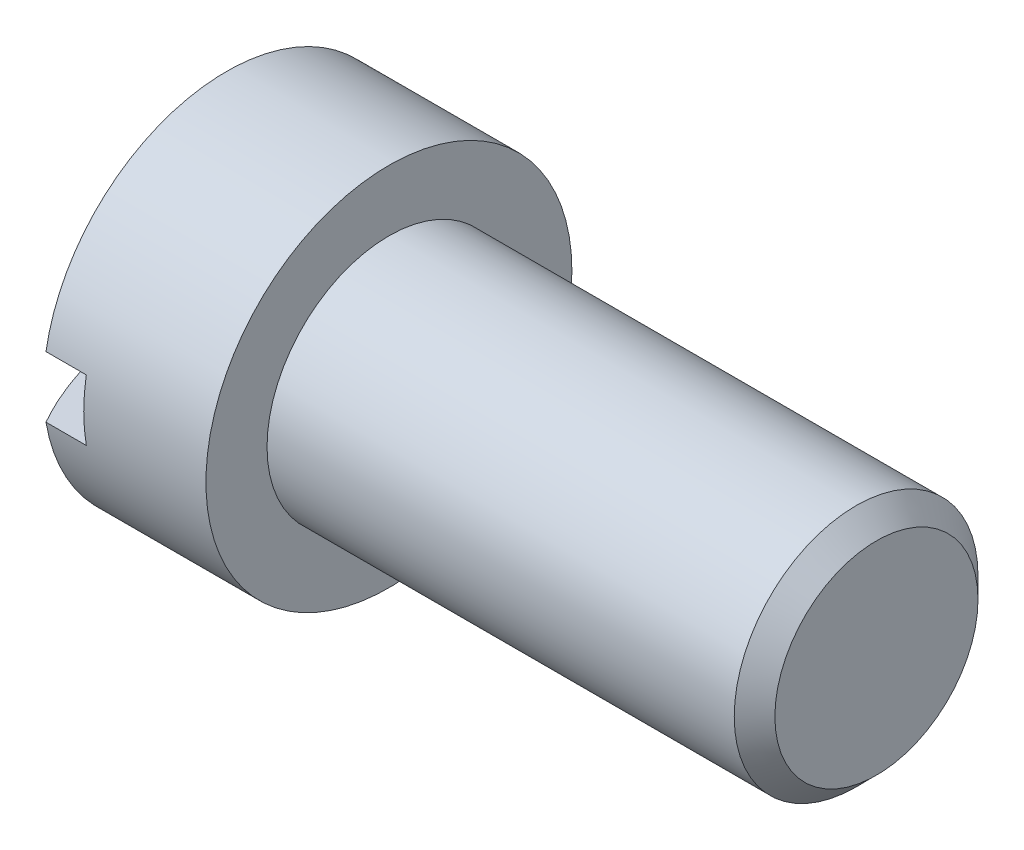
SolidWorks part; units mm, degrees
material "Alloy Steel"
ref_plane "Front Plane" through (0, 0, 0) normal (0, 0, 1) x (1, 0, 0)
ref_plane "Top Plane" through (0, 0, 0) normal (0, 1, 0) x (1, 0, 0)
ref_plane "Right Plane" through (0, 0, 0) normal (1, 0, 0) x (0, 0, -1)
sketch "Sketch1" plane through (0, 0, 0) normal (0, 0, 1) x (1, 0, 0)
  line L0 (-4.7752, 0) -> (19.05, 0)
  line L1 (19.05, 0) -> (19.05, 4.7625)
  line L2 (19.05, 4.7625) -> (0, 4.7625)
  line L3 (0, 4.7625) -> (0, 7.1501)
  line L4 (0, 7.1501) -> (-6.35, 7.1501)
  line L5 (-7.9502, 1.1938) -> (-4.7752, 1.1938)
  line L6 (-4.7752, 1.1938) -> (-4.7752, 0)
  line L7 (25.6383, 0) -> (-22.8527, 0) construction
  line L8 (-7.9502, 1.1938) -> (-7.9502, 8.3265) construction
  arc A1 (-6.35, 7.1501) -> (-7.9502, 1.1938) centre (3.9352, 1.1938) ccw
  dimension "D1" = 4.7752
  dimension "D2" = 7.9502
  dimension "D3" = 1.1938
  dimension "D4" = 6.35
  dimension "D5" = 19.05
  dimension "D6" = 9.525
  dimension "D7" = 14.3002
revolve "Revolve1" add sketch "Sketch1" angle 360 about L7
cosmetic thread "Cosmetic Thread1" parameters "D1"=12.7, "D2"=8.2652
sketch "Sketch2" plane through (0, 0, 0) normal (0, 0, 1) x (1, 0, 0)
  line L0 (-7.9502, 1.1938) -> (-7.9502, -1.1938) construction
  line L1 (-7.9502, 1.1938) -> (-7.9502, -1.1938)
  line L2 (-4.7752, 1.1938) -> (-4.7752, -1.1938) construction
  line L3 (-4.7752, 1.1938) -> (-4.7752, -1.1938)
  line L4 (-7.9502, 1.1938) -> (-4.7752, 1.1938)
  line L5 (-7.9502, -1.1938) -> (-4.7752, -1.1938)
extrude "Cut-Extrude1" cut sketch "Sketch2" against normal through all and the other way through all
chamfer "Chamfer1" distance 0.7937 angle 45 1 edges at (19.05, 0, -4.7625)
